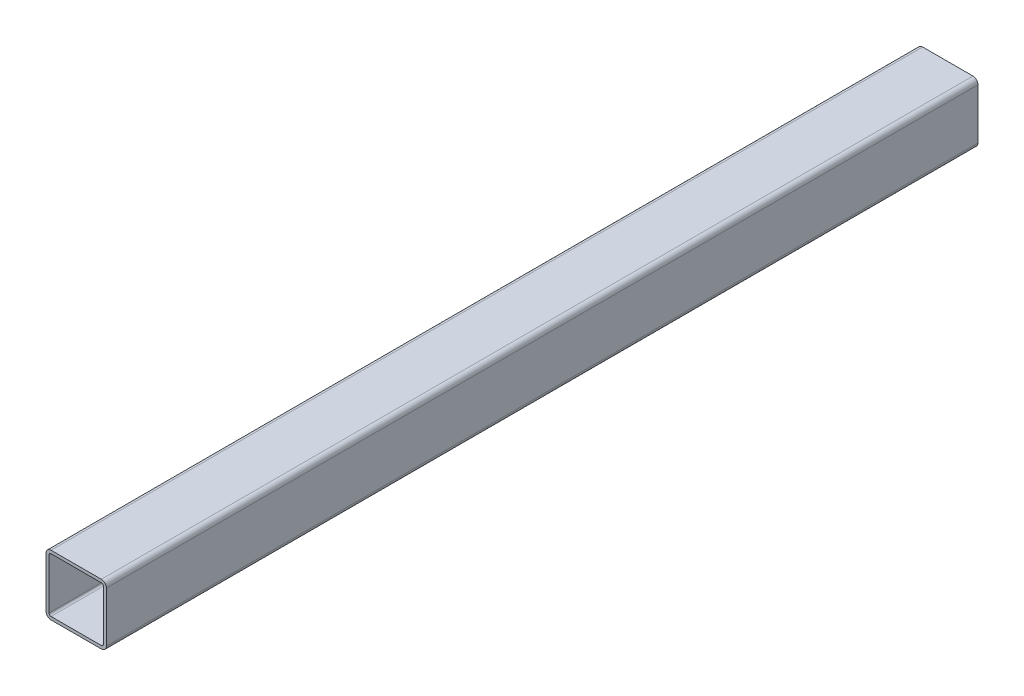
SolidWorks part; units mm, degrees
material "1.0117 (S235J2G4)"
ref_plane "Спереди" through (0, 0, 0) normal (0, 0, 1) x (1, 0, 0)
ref_plane "Сверху" through (0, 0, 0) normal (0, 1, 0) x (1, 0, 0)
ref_plane "Справа" through (0, 0, 0) normal (1, 0, 0) x (0, 0, -1)
sketch "Эскиз1" plane through (0, 0, 0) normal (0, 0, 1) x (1, 0, 0)
  line L0 (25, -6000) -> (-25, -6000) construction
  point P4 (0, -6000)
  point P11 (30, 30)
  point P18 (30, -30)
  line B0 (-25, -30) -> (25, -30)
  line B1 (-30, -25) -> (-30, 25)
  line B2 (-25, 30) -> (25, 30)
  line B3 (30, -25) -> (30, 25)
  line B4 (30, 0) -> (-30, 0) construction
  arc B5 (25, 30) -> (30, 25) centre (25, 25) cw
  arc B6 (-30, 25) -> (-25, 30) centre (-25, 25) cw
  arc B7 (-25, -30) -> (-30, -25) centre (-25, -25) cw
  arc B8 (25, -30) -> (30, -25) centre (25, -25) ccw
  dimension "D1" = 60
sketch_block_instance "Блок1-1"
sketch_block "Блок1" parameters "D1"=5
extrude "Бобышка-Вытянуть1" add sketch "Эскиз1" along normal mid plane 866
shell "Оболочка1" thickness 3
sketch "Эскиз3" plane through (0, 0, 0) normal (0, 1, 0) x (1, 0, 0)
  line L0 (0, 0) -> (0, -433) construction
  line L1 (25, -433) -> (-25, -433) construction
  line L2 (0, 0) -> (0, 30) construction
  line L3 (0, -433) -> (0, -463) construction
  dimension "D1" = 30
  dimension "D2" = 30
sketch "Эскиз4" plane through (0, 30, 0) normal (0, 1, 0) x (1, 0, 0)
  line L0 (0, -433) -> (0, 433) construction
  line L1 (25, -433) -> (-25, -433) construction
  line L2 (25, 433) -> (-25, 433) construction
sketch "Эскиз5" plane through (0, -30, 0) normal (0, -1, 0) x (-1, 0, 0)
  line L0 (0, -862.0825) -> (0, 433) construction
  line L1 (25, 433) -> (-25, 433) construction
  line L2 (-25, 0) -> (0, 0) construction
  line L3 (-25, -433) -> (-25, 433) construction
